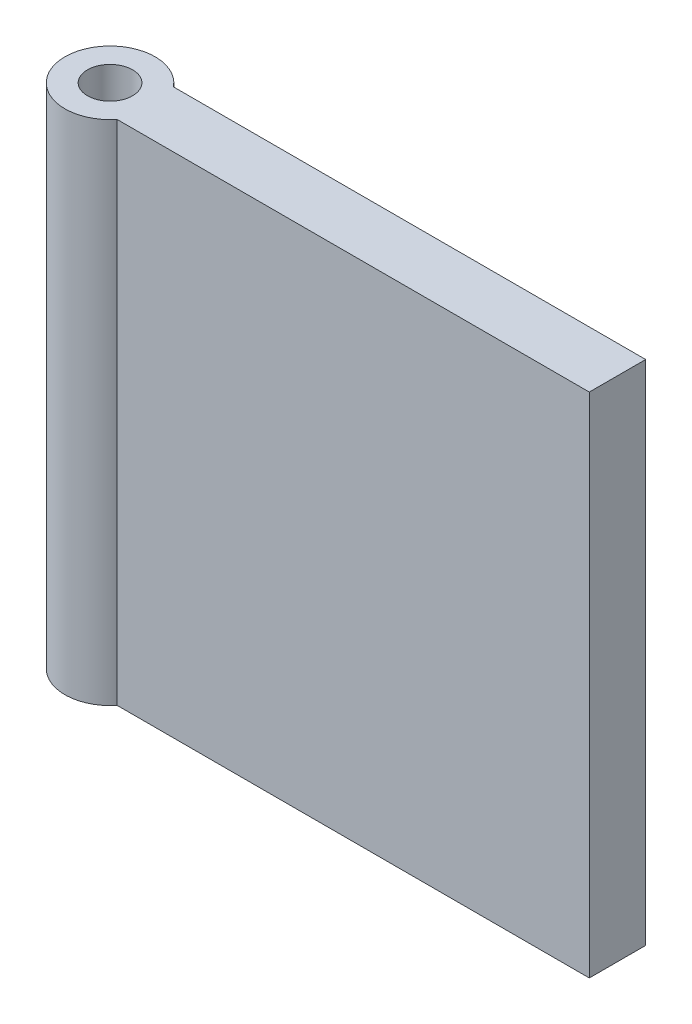
SolidWorks part; units mm, degrees
ref_plane "Front Plane" through (0, 0, 0) normal (0, 0, 1) x (1, 0, 0)
ref_plane "Top Plane" through (0, 0, 0) normal (0, 1, 0) x (1, 0, 0)
ref_plane "Right Plane" through (0, 0, 0) normal (1, 0, 0) x (0, 0, -1)
sketch "Sketch2" plane through (0, 0, 0) normal (0, 1, 0) x (1, 0, 0)
  line L0 (0, 0) -> (36.6797, 0) construction
  line L1 (45, -2.5) -> (0, -2.5)
  line L2 (45, -2.5) -> (45, 2.5)
  line L3 (45, 2.5) -> (0, 2.5)
  line L4 (0, -2.5) -> (0, 2.5)
  circle A0 centre (0, 0) radius 4
  point P7 (0, 0)
  dimension "D1" = 5
  dimension "D2" = 8
  dimension "D3" = 45
extrude "Boss-Extrude1" add sketch "Sketch2" along normal blind 45 contours L0 A0 L1 L2 | L3 A0 L1 L4 | L0 L4 L1 A0 | L4 L0 A0 L3 | A0 L0 L2 L3
sketch "Sketch3" plane through (0, 45, 0) normal (0, 1, 0) x (1, 0, 0)
  circle A0 centre (0, 0) radius 2
extrude "Cut-Extrude1" cut sketch "Sketch3" against normal through all
